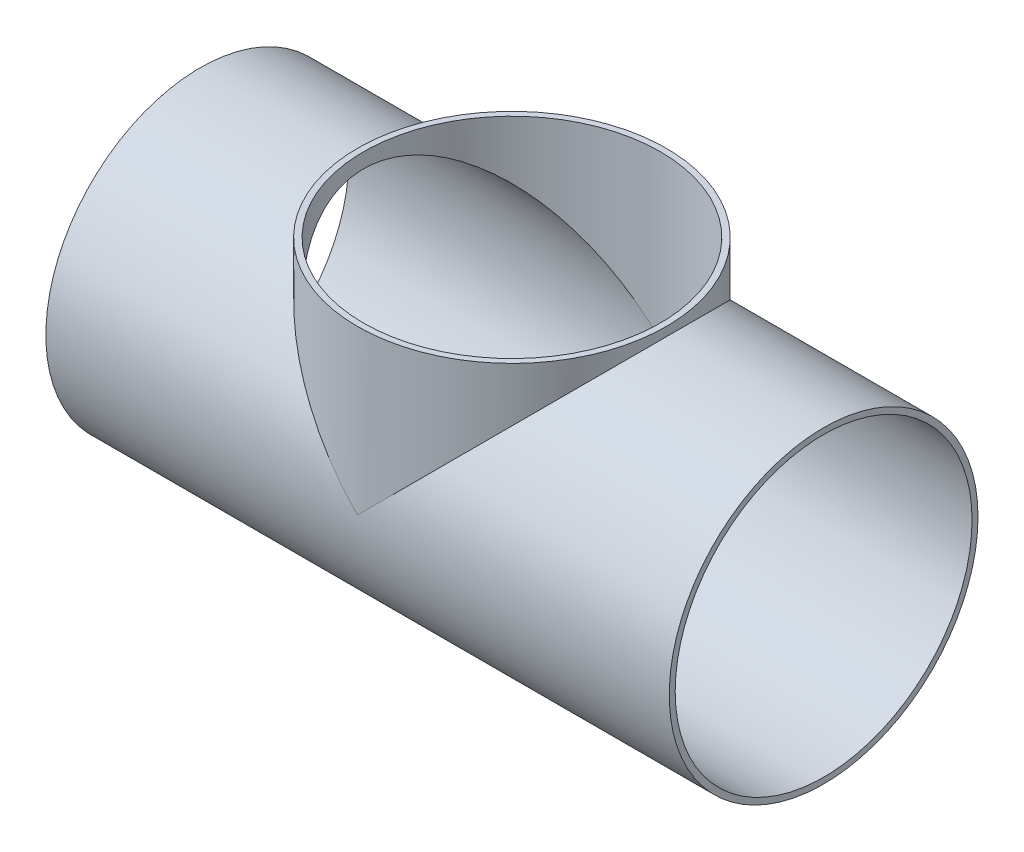
SolidWorks part; units mm, degrees
ref_plane "Front Plane" through (0, 0, 0) normal (0, 0, 1) x (1, 0, 0)
ref_plane "Top Plane" through (0, 0, 0) normal (0, 1, 0) x (1, 0, 0)
ref_plane "Right Plane" through (0, 0, 0) normal (1, 0, 0) x (0, 0, -1)
sketch "Sketch1" plane through (0, 0, 0) normal (0, 0, 1) x (1, 0, 0)
  line L0 (0, 52) -> (0, 0)
  line L1 (0, 0) -> (210, 0)
  line L2 (210, 0) -> (210, 52)
  line L3 (210, 52) -> (0, 52)
  line L4 (0, 0) -> (210, 0) construction
  dimension "D1" = 210
  dimension "D2" = 52
revolve "Revolve1" add sketch "Sketch1" angle 360 about L4
sketch "Sketch2" plane through (0, 0, 0) normal (0, 0, 1) x (1, 0, 0)
  line L0 (105, 55) -> (53, 55)
  line L1 (53, 55) -> (53, 0)
  line L2 (53, 0) -> (105, 0)
  line L3 (105, 0) -> (105, 55)
  line L4 (105, 0) -> (105, 55) construction
  line L5 (53, 0) -> (0, 0) construction
  dimension "D1" = 52
  dimension "D2" = 55
revolve "Revolve2" add sketch "Sketch2" angle 360 about L4
hole_wizard "M90 Clearance Hole1" positions "Sketch4" profile "Sketch3" hole size "M90" standard "ANSI Metric"
sketch "Sketch4" plane through (210, 0, 0) normal (1, 0, 0) x (0, 0, -1)
  point P0 (0, 0)
sketch "Sketch3" plane through (210, 0, 0) normal (0, 1, 0) x (0, 0, -1)
  line L0 (0, 0) -> (0, 210)
  line L1 (0, 210) -> (50, 210)
  line L2 (50, 210) -> (50, 0)
  line L5 (50, 0) -> (0, 0)
  line L11 (0, -6.35) -> (0, 107.95) construction
  dimension "Thru Hole Dia." = 100
  dimension "Thru Hole Depth" = 210
hole_wizard "M90 Clearance Hole2" positions "Sketch6" profile "Sketch5" hole size "M90" standard "ANSI Metric"
sketch "Sketch6" plane through (0, 55, 0) normal (0, 1, 0) x (1, 0, 0)
  point P0 (105, 0)
sketch "Sketch5" plane through (105, 55, 0) normal (1, 0, 0) x (0, 0, 1)
  line L0 (0, 0) -> (0, 5)
  line L1 (0, 5) -> (50, 5)
  line L2 (50, 5) -> (50, 0)
  line L5 (50, 0) -> (0, 0)
  line L11 (0, -6.35) -> (0, 107.95) construction
  dimension "Thru Hole Dia." = 100
  dimension "Thru Hole Depth" = 5
ref_plane "Plane1" through (105, 0, 0) normal (1, 0, 0) x (0, 0, -1)
